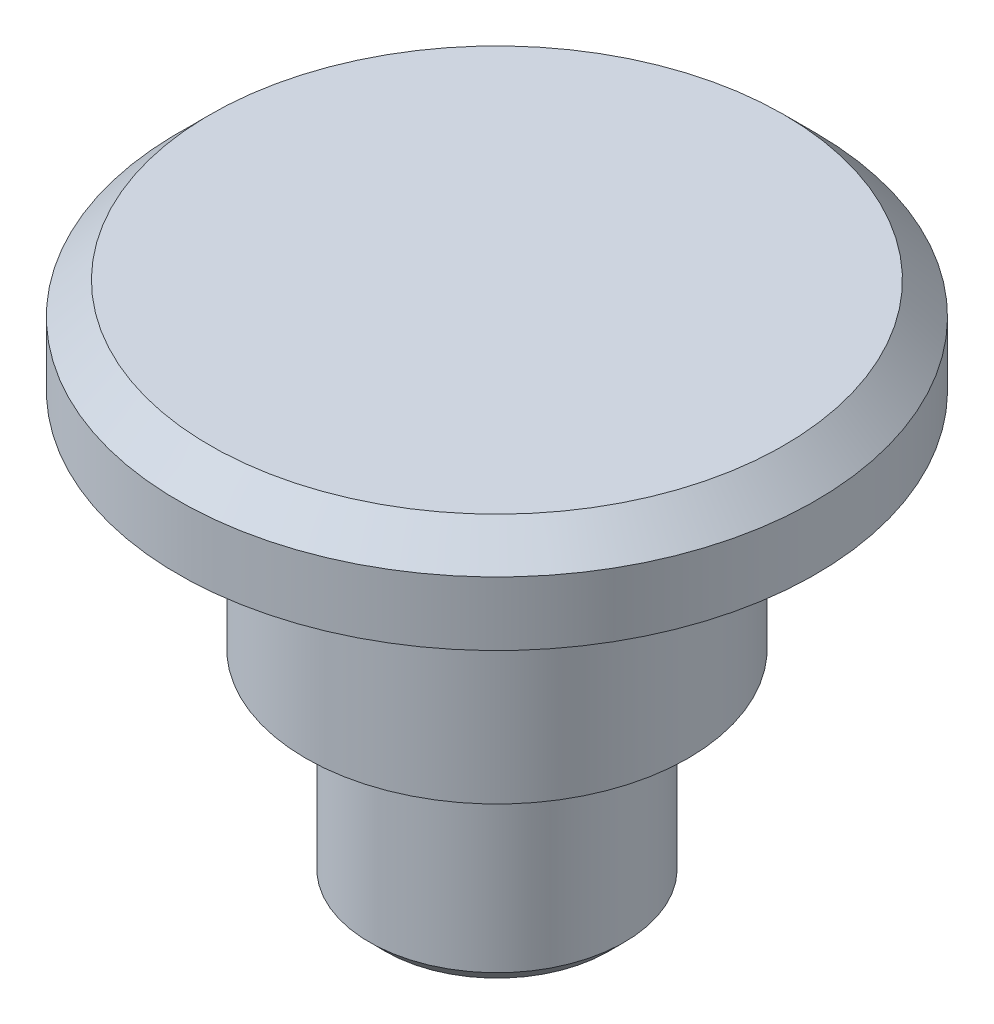
SolidWorks part; units mm, degrees
ref_plane "Plan1" through (0, 0, 0) normal (0, 0, 1) x (1, 0, 0)
ref_plane "Plan2" through (0, 0, 0) normal (0, 1, 0) x (1, 0, 0)
ref_plane "Plan3" through (0, 0, 0) normal (1, 0, 0) x (0, 0, -1)
sketch "Esquisse1" plane through (0, 0, 0) normal (0, 0, 1) x (1, 0, 0)
  line L0 (0, 0) -> (0, 100) construction
  line L1 (0, 0) -> (3.5, 0)
  line L2 (4, 0.5) -> (4, 6.5)
  line L3 (6, 6.5) -> (6, 13.5)
  line L4 (6.6, 13.5) -> (10, 13.5)
  line L5 (10, 15.5) -> (10, 13.5)
  line L7 (9, 16.5) -> (0, 16.5)
  line L8 (0, 16.5) -> (0, 0)
  line L9 (6, 6.5) -> (4.6, 6.5)
  line L10 (9, 16.5) -> (10, 15.5)
  line L11 (3.5, 0) -> (4, 0.5)
  arc A0 (4.6, 6.5) -> (4, 6.5) centre (4.3, 6.5) ccw
  arc A1 (6.6, 13.5) -> (6, 13.5) centre (6.3, 13.5) ccw
  point P3 (4, 0)
  dimension "D4" = 0.3
  dimension "D5" = 6
  dimension "D6" = 0.3
  dimension "D1" = 6.5
  dimension "D2" = 7
  dimension "D3" = 3
  dimension "D7" = 4
  dimension "D8" = 10
  dimension "D12" = 0.5
revolve "Base-Révolution" add sketch "Esquisse1" angle 360 about L0
